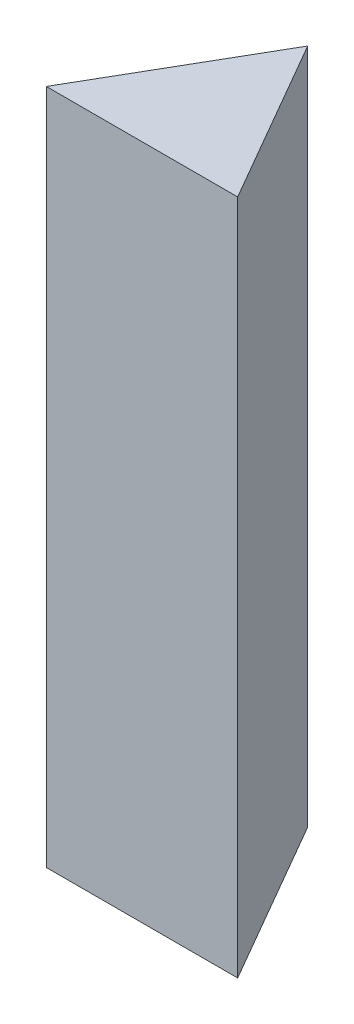
SolidWorks part; units mm, degrees
ref_plane "Front" through (0, 0, 0) normal (0, 0, 1) x (1, 0, 0)
ref_plane "Top" through (0, 0, 0) normal (0, 1, 0) x (1, 0, 0)
ref_plane "Right" through (0, 0, 0) normal (1, 0, 0) x (0, 0, -1)
sketch "Sketch1" plane through (0, 0, 0) normal (0, 1, 0) x (1, 0, 0)
  line L0 (0, 2.45) -> (-2.1218, -1.225)
  line L1 (-2.1218, -1.225) -> (2.1218, -1.225)
  line L2 (2.1218, -1.225) -> (0, 2.45)
  circle A0 centre (0, 0) radius 2.45
  dimension "D1" = 4.9
  dimension "D2" = 60
extrude "Boss-Extrude1" add sketch "Sketch1" along normal blind 15 contours L1 L2 L0
